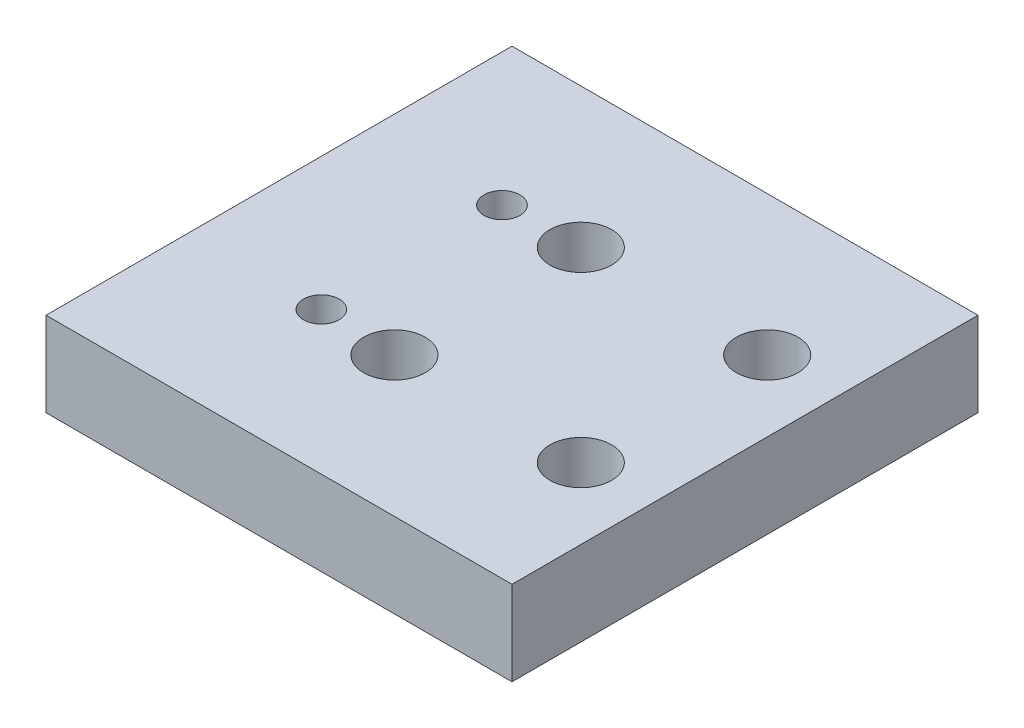
SolidWorks part; units mm, degrees
ref_plane "Front" through (0, 0, 0) normal (0, 0, 1) x (1, 0, 0)
ref_plane "Top" through (0, 0, 0) normal (0, 1, 0) x (1, 0, 0)
ref_plane "Right" through (0, 0, 0) normal (1, 0, 0) x (0, 0, -1)
sketch "Sketch1" plane through (0, 0, 0) normal (0, 1, 0) x (1, 0, 0)
  line L0 (0, 32.5) -> (0, -32.5) construction
  line L1 (-32.5, 32.5) -> (32.5, 32.5)
  line L2 (-32.5, 32.5) -> (-32.5, -32.5)
  line L3 (-32.5, -32.5) -> (32.5, -32.5)
  line L4 (32.5, 32.5) -> (32.5, -32.5)
  dimension "D1" = 65
extrude "Extrude1" add sketch "Sketch1" along normal blind 11.7824
hole_wizard "M6x1.0 Tapped Hole1" positions "Sketch3" profile "Sketch2" tap size "M6x1.0" standard "Ansi Metric" end condition through all
sketch "Sketch3" plane through (0, 11.7824, 0) normal (0, 1, 0) x (-1, 0, 0)
  line L0 (14, -15.9) -> (14, -9.3) construction
  line L1 (17, -15.9) -> (11, -15.9) construction
  line L2 (11, -9.3) -> (17, -9.3) construction
  line L4 (14, 9.3) -> (14, 15.9) construction
  line L5 (17, 9.3) -> (11, 9.3) construction
  line L6 (11, 15.9) -> (17, 15.9) construction
  point P0 (14, -12.6)
  point P1 (14, 12.6)
sketch "Sketch2" plane through (-14, 11.7824, -12.6) normal (1, 0, 0) x (0, 0, 1)
  line L0 (0, 0) -> (0, 11.7824)
  line L1 (0, 11.7824) -> (2.5, 11.7824)
  line L2 (2.5, 11.7824) -> (2.5, 0)
  line L5 (2.5, 0) -> (0, 0)
  line L11 (0, -6.35) -> (0, 107.95) construction
  dimension "Thread Major Dia." = 5
  dimension "Thru Tap Drill Depth" = 11.7824
sketch "Sketch4" plane through (0, 0, 0) normal (0, -1, 0) x (1, 0, 0)
  line L0 (-5.6566, -13) -> (-1.1486, -13) construction
  line L1 (-5.6566, -10) -> (-1.1486, -10)
  line L2 (-5.6566, -10) -> (-5.6566, -16)
  line L3 (-5.6566, -16) -> (-1.1486, -16)
  line L4 (-1.1486, -10) -> (-1.1486, -16)
  line L5 (-3.4026, -13) -> (-5.0236, -13) construction
  line L6 (-3.4026, -13) -> (-3.4026, -10.0257) construction
  line L7 (-3.4026, -10) -> (-3.4026, -16) construction
  circle A1 centre (-3.4026, -13) radius 1.621 construction
  dimension "D1" = 4.508
  dimension "D2" = 6
hole_wizard "CBORE for M4 SBHCS1" positions "Sketch6" profile "Sketch5" counterbore size "M4" standard "Ansi Metric" end condition through all
sketch "Sketch6" plane through (0, 11.7824, 0) normal (0, 1, 0) x (-1, 0, 0)
  point P1 (3.4026, 13)
  point P4 (-22.5974, 13)
  point P7 (-22.5974, -13)
  point P10 (3.4026, -13)
sketch "Sketch5" plane through (-3.4026, 11.7824, 13) normal (1, 0, 0) x (0, 0, 1)
  line L0 (0, 0) -> (0, 11.7824)
  line L1 (0, 11.7824) -> (2.4, 11.7824)
  line L3 (2.4, 11.7824) -> (2.4, 8.2)
  line L4 (2.4, 8.2) -> (4.3, 8.2)
  line L5 (4.3, 8.2) -> (4.3, 0)
  line L7 (4.3, 0) -> (0, 0)
  line L11 (0, -6.35) -> (0, 107.95) construction
  dimension "Thru Hole Dia." = 4.8
  dimension "Thru Hole Depth" = 11.7824
  dimension "C'Bore Dia." = 8.6
  dimension "C'Bore Depth" = 8.2
